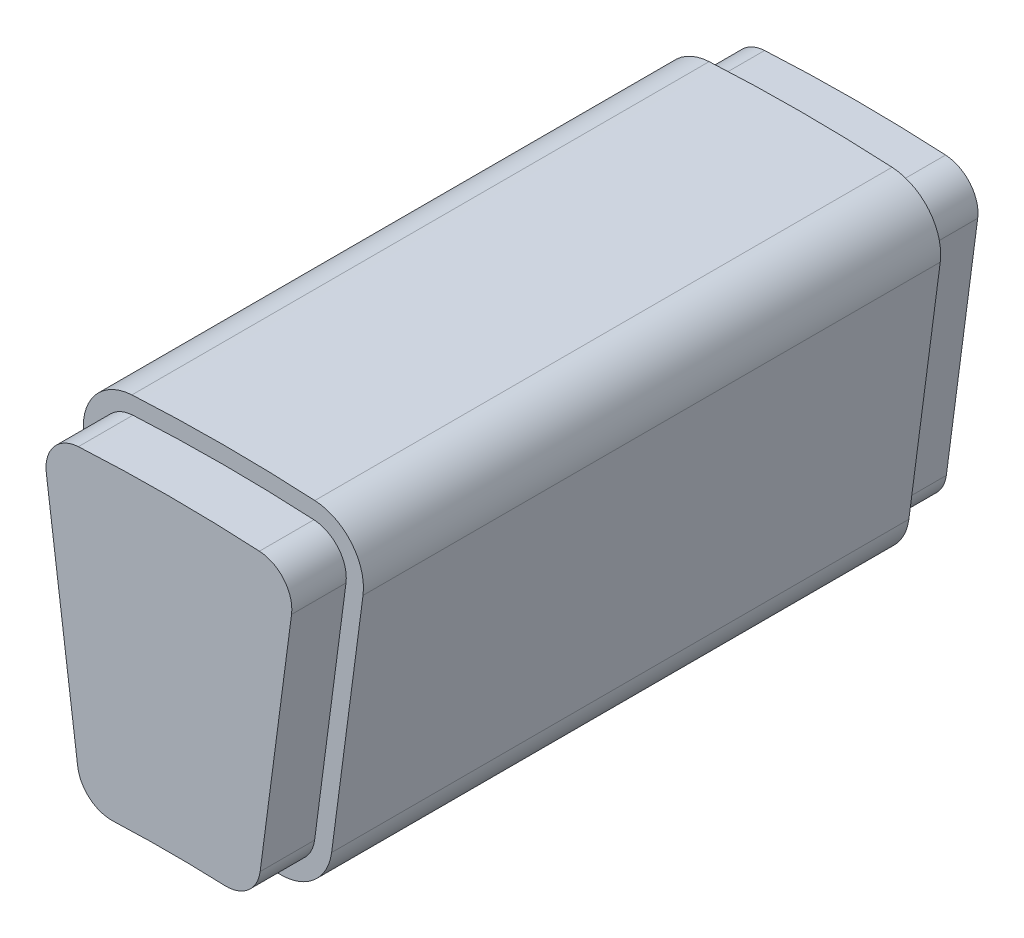
SolidWorks part; units mm, degrees
material "Plain Carbon Steel"
ref_plane "Front Plane" through (0, 0, 0) normal (0, 0, 1) x (1, 0, 0)
ref_plane "Top Plane" through (0, 0, 0) normal (0, 1, 0) x (1, 0, 0)
ref_plane "Right Plane" through (0, 0, 0) normal (1, 0, 0) x (0, 0, -1)
sketch "Sketch1" plane through (0, 0, 0) normal (0, 0, 1) x (1, 0, 0)
  line L3 (5.3187, 78.7059) -> (7.1481, 92.602)
  line L4 (-7.1481, 92.602) -> (-5.3187, 78.7059)
  line L5 (5.3187, 78.7059) -> (7.1481, 92.602)
  line L6 (-7.1481, 92.602) -> (-5.3187, 78.7059)
  arc A6 (5.2763, 94.86) -> (-5.2763, 94.86) centre (0, 0) ccw
  arc A7 (7.1481, 92.602) -> (5.2763, 94.86) centre (5.1652, 92.863) ccw
  arc A8 (3.2514, 76.9687) -> (5.3187, 78.7059) centre (3.3358, 78.9669) ccw
  arc A9 (3.2514, 76.9687) -> (-3.2514, 76.9687) centre (0, 0) ccw
  arc A10 (-5.3187, 78.7059) -> (-3.2514, 76.9687) centre (-3.3358, 78.9669) ccw
  arc A11 (-5.2763, 94.86) -> (-7.1481, 92.602) centre (-5.1652, 92.863) ccw
  arc A12 (5.2763, 94.86) -> (-5.2763, 94.86) centre (0, 0) ccw
  arc A13 (7.1481, 92.602) -> (5.2763, 94.86) centre (5.1652, 92.863) ccw
  arc A14 (3.2514, 76.9687) -> (5.3187, 78.7059) centre (3.3358, 78.9669) ccw
  arc A15 (3.2514, 76.9687) -> (-3.2514, 76.9687) centre (0, 0) ccw
  arc A16 (-5.3187, 78.7059) -> (-3.2514, 76.9687) centre (-3.3358, 78.9669) ccw
  arc A17 (-5.2763, 94.86) -> (-7.1481, 92.602) centre (-5.1652, 92.863) ccw
  dimension "D1" = 0
extrude "Boss-Extrude1" add sketch "Sketch1" against normal up to vertex (3.175 mm away) and the other way up to vertex (36.825 mm away)
sketch "Sketch2" plane through (0, 0, 0) normal (0, 0, 1) x (1, 0, 0)
  line L4 (6.3101, 78.5753) -> (8.1396, 92.4715)
  line L5 (-8.1396, 92.4715) -> (-6.3101, 78.5753)
  line L6 (6.3101, 78.5753) -> (8.1396, 92.4715)
  line L7 (-8.1396, 92.4715) -> (-6.3101, 78.5753)
  arc A12 (8.1396, 92.4715) -> (5.3319, 95.8584) centre (5.1652, 92.863) ccw
  arc A13 (3.2092, 75.9696) -> (6.3101, 78.5753) centre (3.3358, 78.9669) ccw
  arc A14 (3.2092, 75.9696) -> (-3.2092, 75.9696) centre (0, 0) ccw
  arc A15 (-6.3101, 78.5753) -> (-3.2092, 75.9696) centre (-3.3358, 78.9669) ccw
  arc A16 (-5.3319, 95.8584) -> (-8.1396, 92.4715) centre (-5.1652, 92.863) ccw
  arc A17 (5.3319, 95.8584) -> (-5.3319, 95.8584) centre (0, 0) ccw
  arc A18 (8.1396, 92.4715) -> (5.3319, 95.8584) centre (5.1652, 92.863) ccw
  arc A19 (3.2092, 75.9696) -> (6.3101, 78.5753) centre (3.3358, 78.9669) ccw
  arc A20 (3.2092, 75.9696) -> (-3.2092, 75.9696) centre (0, 0) ccw
  arc A21 (-6.3101, 78.5753) -> (-3.2092, 75.9696) centre (-3.3358, 78.9669) ccw
  arc A22 (-5.3319, 95.8584) -> (-8.1396, 92.4715) centre (-5.1652, 92.863) ccw
  arc A23 (5.3319, 95.8584) -> (-5.3319, 95.8584) centre (0, 0) ccw
  dimension "D1" = 1
extrude "Boss-Extrude2" add sketch "Sketch2" along normal up to vertex (33.65 mm away)
